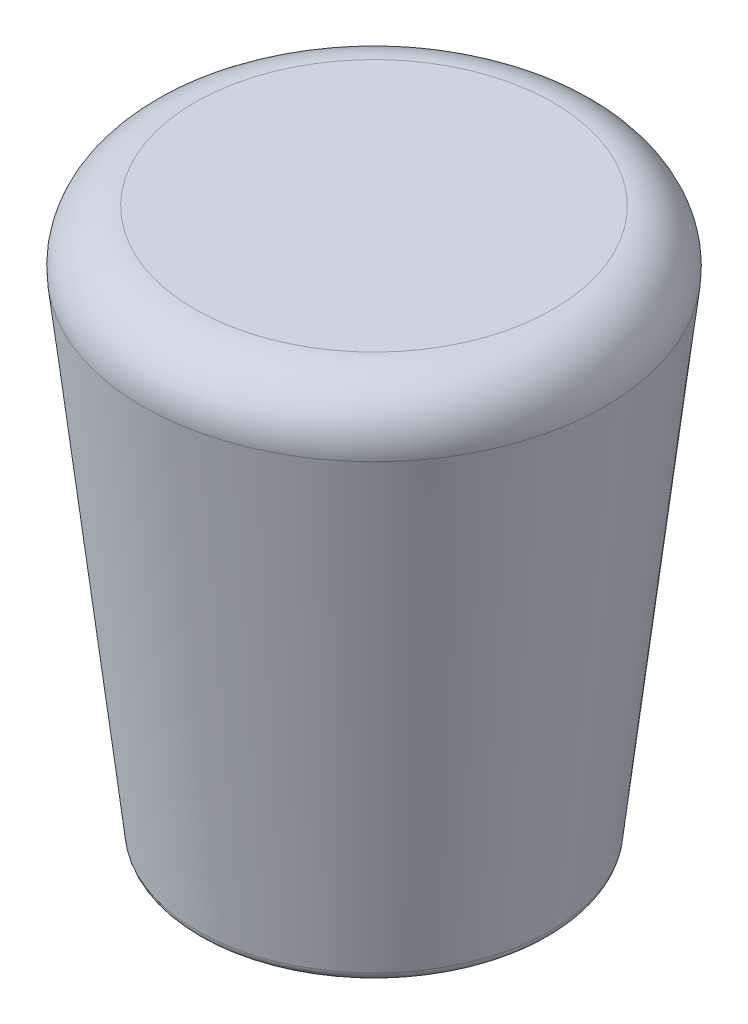
SolidWorks part; units mm, degrees
material "ABS"
ref_plane "Спереди" through (0, 0, 0) normal (0, 0, 1) x (1, 0, 0)
ref_plane "Сверху" through (0, 0, 0) normal (0, 1, 0) x (1, 0, 0)
ref_plane "Справа" through (0, 0, 0) normal (1, 0, 0) x (0, 0, -1)
sketch "Эскиз1" plane through (0, 0, 0) normal (0, 1, 0) x (1, 0, 0)
  circle A0 centre (0, 0) radius 3.35
  dimension "D1" = 6.7
extrude "Бобышка-Вытянуть1" add sketch "Эскиз1" along normal blind 10.5 draft 6.5 draft outward yes
sketch "Эскиз2" plane through (0, 0, 0) normal (0, -1, 0) x (1, 0, 0)
  circle A0 centre (0, 0) radius 3
  dimension "D1" = 6
extrude "Вырез-Вытянуть1" cut sketch "Эскиз2" against normal blind 9
fillet "Скругление1" radius 1 1 edges at (0, 10.5, 4.5463)
fillet "Скругление2" radius 0.2 1 edges at (0, 0, 3.35)
